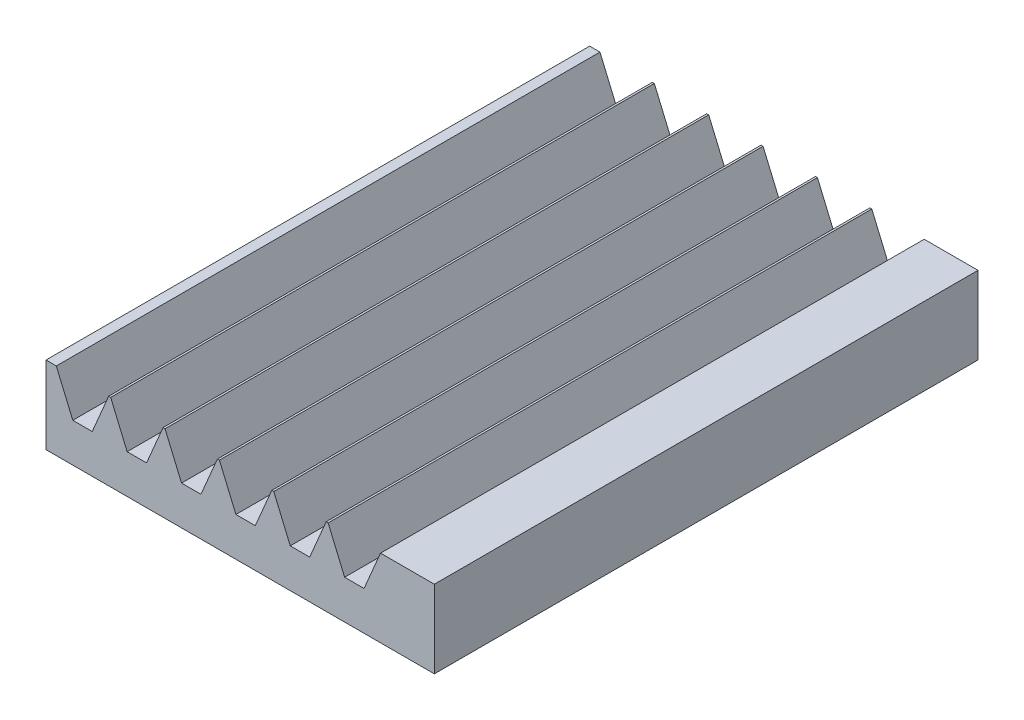
SolidWorks part; units mm, degrees
ref_plane "Front Plane" through (0, 0, 0) normal (0, 0, 1) x (1, 0, 0)
ref_plane "Top Plane" through (0, 0, 0) normal (0, 1, 0) x (1, 0, 0)
ref_plane "Right Plane" through (0, 0, 0) normal (1, 0, 0) x (0, 0, -1)
sketch "Sketch1" plane through (0, 0, 0) normal (0, 0, 1) x (1, 0, 0)
  line L14 (0, 0) -> (10, 0)
  line L15 (0, 0) -> (0, 2)
  line L16 (0, 2) -> (10, 2)
  line L17 (10, 0) -> (10, 2)
  dimension "D1" = 10
  dimension "D2" = 2
extrude "Boss-Extrude1" add sketch "Sketch1" along normal blind 5 and the other way blind 9
sketch "Sketch3" plane through (0, 0, 5) normal (0, 0, 1) x (1, 0, 0)
  line L0 (0.9398, 2) -> (0.9398, 1) construction
  line L1 (10, 2) -> (0, 2) construction
  line L2 (0.6898, 1) -> (1.1898, 1)
  line L3 (0.6898, 1) -> (0.26, 2.0126)
  line L4 (0.26, 2.0126) -> (1.6196, 2.0126)
  line L5 (1.6196, 2.0126) -> (1.1898, 1)
  line L6 (0.9398, 2) -> (0.9398, 2.0126) construction
  point P7 (0.9398, 1)
  dimension "D1" = 1
  dimension "D2" = 0.5
  dimension "D3" = 113
  dimension "D4" = 1.1
extrude "Cut-Extrude1" cut sketch "Sketch3" against normal blind 18
pattern_linear "LPattern2" count 6 spacing 1.4 along (1, 0, 0) of "Cut-Extrude1"
